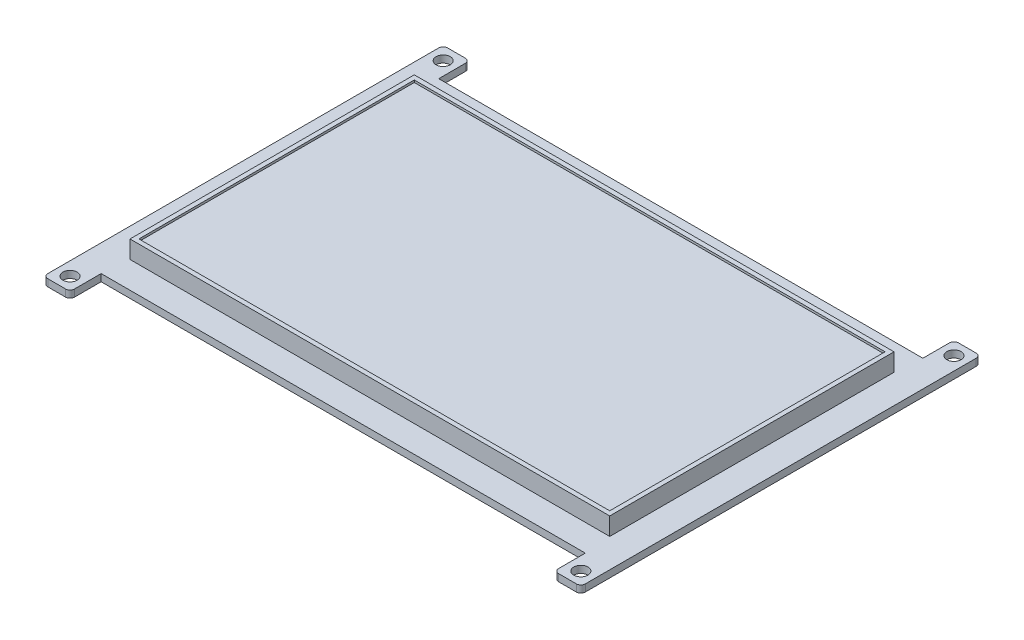
SolidWorks part; units mm, degrees
ref_plane "前视基准面" through (0, 0, 0) normal (0, 0, 1) x (1, 0, 0)
ref_plane "上视基准面" through (0, 0, 0) normal (0, 1, 0) x (1, 0, 0)
ref_plane "右视基准面" through (0, 0, 0) normal (1, 0, 0) x (0, 0, -1)
sketch "草图1" plane through (0, 0, 0) normal (0, 1, 0) x (1, 0, 0)
  line L0 (54.5, 38) -> (-54.5, 38)
  line L1 (-54.5, 38) -> (-54.5, 44)
  line L2 (-55.5, 45) -> (-59.5, 45)
  line L3 (-60.5, 44) -> (-60.5, -44)
  line L4 (-88.4059, 0) -> (70.5461, 0) construction
  line L5 (-57.5, 45) -> (-57.5, 29.8047) construction
  line L6 (-57.5, -45) -> (-57.5, -29.8047) construction
  line L7 (-55.5, -45) -> (-59.5, -45)
  line L8 (-54.5, -38) -> (-54.5, -44)
  line L9 (54.5, -38) -> (-54.5, -38)
  line L10 (0, 38) -> (0, -48.3864) construction
  line L11 (-115, -38) -> (-60.5, -38)
  line L12 (-60.5, 38) -> (-60.5, 44)
  line L13 (-115, 38) -> (-60.5, 38)
  line L14 (57.5, -45) -> (57.5, -29.8047) construction
  line L15 (57.5, 45) -> (57.5, 29.8047) construction
  line L16 (60.5, 38) -> (60.5, 44)
  line L17 (54.5, -38) -> (54.5, -44)
  line L18 (55.5, -45) -> (59.5, -45)
  line L19 (60.5, 44) -> (60.5, -44)
  line L20 (55.5, 45) -> (59.5, 45)
  line L21 (54.5, 38) -> (54.5, 44)
  circle A0 centre (-57.5, 42) radius 1.6
  arc A1 (-54.5, 44) -> (-55.5, 45) centre (-55.5, 44) ccw
  arc A2 (-60.5, 44) -> (-59.5, 45) centre (-59.5, 44) cw
  arc A3 (-60.5, -44) -> (-59.5, -45) centre (-59.5, -44) ccw
  arc A4 (-54.5, -44) -> (-55.5, -45) centre (-55.5, -44) cw
  circle A5 centre (-57.5, -42) radius 1.6
  arc A6 (-54.5, 44) -> (-55.5, 45) centre (-55.5, 44) ccw
  arc A7 (-60.5, 44) -> (-59.5, 45) centre (-59.5, 44) cw
  arc A8 (60.5, 44) -> (59.5, 45) centre (59.5, 44) ccw
  arc A9 (54.5, 44) -> (55.5, 45) centre (55.5, 44) cw
  circle A10 centre (57.5, -42) radius 1.6
  arc A11 (54.5, -44) -> (55.5, -45) centre (55.5, -44) ccw
  arc A12 (60.5, -44) -> (59.5, -45) centre (59.5, -44) cw
  arc A13 (60.5, 44) -> (59.5, 45) centre (59.5, 44) ccw
  arc A14 (54.5, 44) -> (55.5, 45) centre (55.5, 44) cw
  circle A15 centre (57.5, 42) radius 1.6
  point P12 (0, -48.3864)
  point P27 (-60.5, 0)
  point P30 (-54.5, 0)
  point P57 (0, -38)
  point P58 (54.5, 0)
  point P59 (60.5, 0)
  dimension "D3" = 3.2
  dimension "D4" = 42
  dimension "D5" = 57.5
  dimension "D6" = 1
  dimension "D1" = 60.5
  dimension "D2" = 38
  dimension "D7" = 7
extrude "凸台-拉伸1" add sketch "草图1" along normal blind 1.6 contours A12 L19 L16 A8 L20 A9 L21 L0 L1 A1 L2 A2 L3 A3 L7 A4 L8 L9 L17 A11 L18 A5 A0 A10 A15
sketch "草图2" plane through (0, 1.6, 0) normal (0, 1, 0) x (1, 0, 0)
  line L0 (-60.5, 0) -> (60.5, 0) construction
  line L1 (-60.5, 44) -> (-60.5, -44) construction
  line L2 (60.5, 44) -> (60.5, -44) construction
  line L3 (0, 38) -> (0, -38) construction
  line L4 (54.5, 38) -> (-54.5, 38) construction
  line L5 (54.5, -38) -> (-54.5, -38) construction
  line L7 (-54, 32) -> (54, 32)
  line L8 (-54, 32) -> (-54, -32)
  line L9 (-54, -32) -> (54, -32)
  line L10 (54, 32) -> (54, -32)
  line L11 (-54, 32) -> (54, -32) construction
  line L12 (-54, -32) -> (54, 32) construction
  point P12 (0, 0)
  dimension "D1" = 108
  dimension "D2" = 64
extrude "凸台-拉伸2" add sketch "草图2" along normal blind 4
sketch "草图3" plane through (0, 5.6, 0) normal (0, 1, 0) x (1, 0, 0)
  line L0 (-54, -32) -> (54, -32) construction
  line L1 (-53, 31) -> (53, 31)
  line L2 (-53, 31) -> (-53, -31)
  line L3 (-53, -31) -> (53, -31)
  line L4 (53, 31) -> (53, -31)
  line L5 (-53, 31) -> (53, -31) construction
  line L6 (-53, -31) -> (53, 31) construction
  line L7 (54, -32) -> (54, 32) construction
  point P0 (0, 0)
  dimension "D1" = 1
  dimension "D2" = 1
extrude "切除-拉伸1" cut sketch "草图3" against normal blind 0.5
